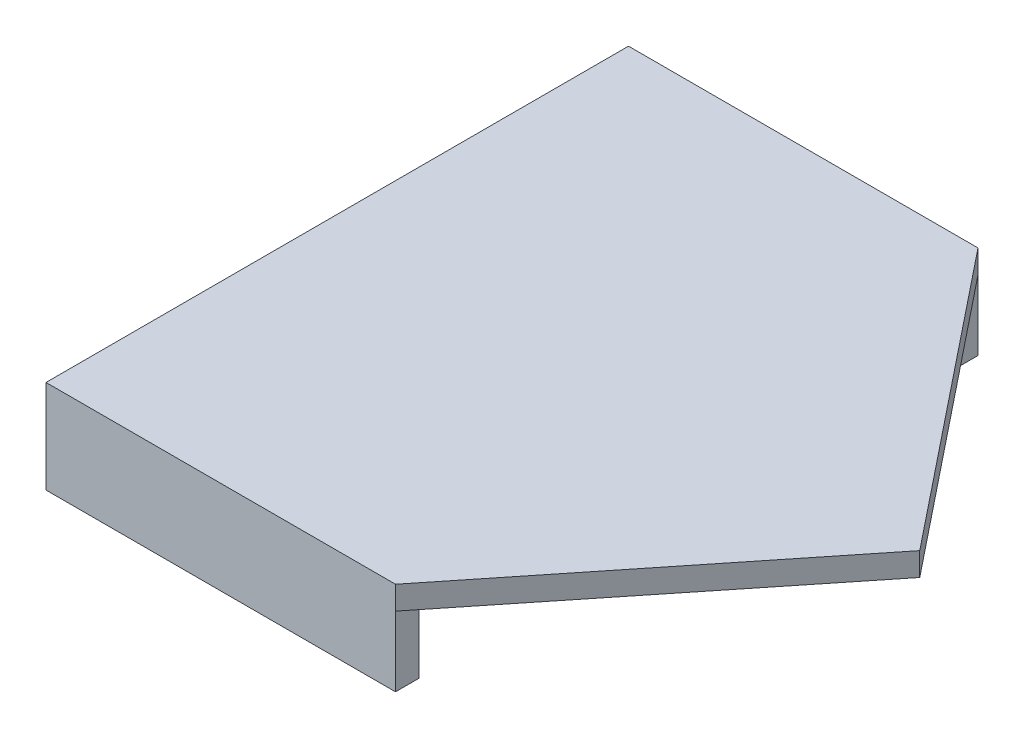
SolidWorks part; units mm, degrees
ref_plane "Front Plane" through (0, 0, 0) normal (0, 0, 1) x (1, 0, 0)
ref_plane "Top Plane" through (0, 0, 0) normal (0, 1, 0) x (1, 0, 0)
ref_plane "Right Plane" through (0, 0, 0) normal (1, 0, 0) x (0, 0, -1)
sketch "Sketch1" plane through (0, 0, 0) normal (0, 1, 0) x (1, 0, 0)
  line L0 (75, 125) -> (175, 0)
  line L1 (-75, -125) -> (75, -125)
  line L2 (-75, -125) -> (-75, 125)
  line L3 (-75, 125) -> (75, 125)
  line L5 (0, -55) -> (0, 55) construction
  line L7 (175, 0) -> (75, -125)
  point P0 (0, 0)
  dimension "D1" = 150
  dimension "D2" = 250
  dimension "D3" = 100
  dimension "D4" = 75
  dimension "D5" = 125
  dimension "D6" = 175
extrude "Boss-Extrude1" add sketch "Sketch1" along normal mid plane 10
sketch "Sketch2" plane through (0, 0, -125) normal (0, 0, -1) x (-1, 0, 0)
  line L0 (-75, -5) -> (75, -5)
  line L1 (75, -5) -> (75, -35)
  line L2 (75, -35) -> (-75, -35)
  line L3 (-75, -35) -> (-75, -5)
  dimension "D1" = 30
extrude "Boss-Extrude2" add sketch "Sketch2" against normal blind 10
mirror "Mirror1" about plane through (0, 0, 0) normal (0, 0, 1) of "Boss-Extrude2"
